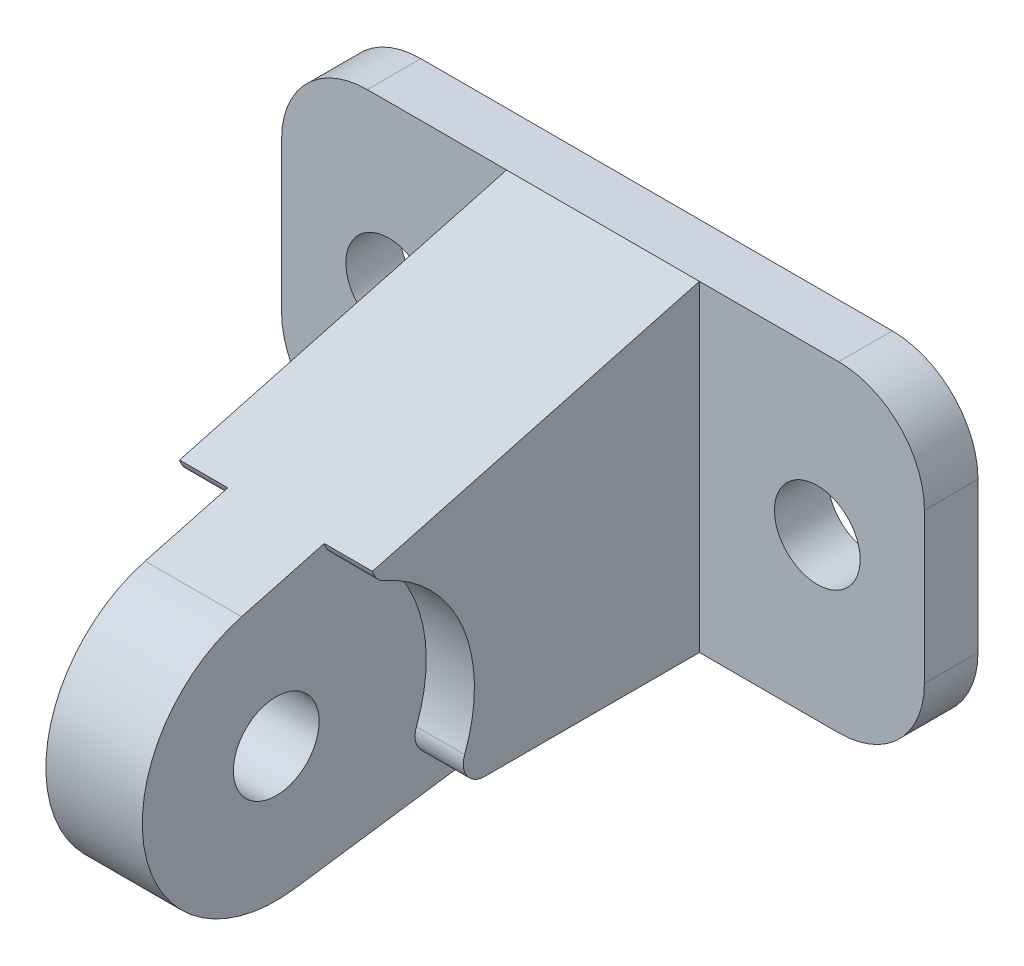
SolidWorks part; units mm, degrees
ref_plane "Płaszczyzna przednia" through (0, 0, 0) normal (0, 0, 1) x (1, 0, 0)
ref_plane "Płaszczyzna górna" through (0, 0, 0) normal (0, 1, 0) x (1, 0, 0)
ref_plane "Płaszczyzna prawa" through (0, 0, 0) normal (1, 0, 0) x (0, 0, -1)
sketch "Szkic1" plane through (0, 0, 0) normal (0, 0, 1) x (1, 0, 0)
  line L1 (-22, 15) -> (22, 15)
  line L2 (-30, 7) -> (-30, -7)
  line L3 (-22, -15) -> (22, -15)
  line L4 (30, 7) -> (30, -7)
  line L5 (-30, 15) -> (30, -15) construction
  line L6 (-30, -15) -> (30, 15) construction
  arc A0 (22, -15) -> (30, -7) centre (22, -7) ccw
  arc A1 (30, 7) -> (22, 15) centre (22, 7) ccw
  arc A2 (-22, -15) -> (-30, -7) centre (-22, -7) cw
  arc A3 (-22, 15) -> (-30, 7) centre (-22, 7) ccw
  circle A4 centre (-20, 0) radius 4
  circle A5 centre (20, 0) radius 4
  point P0 (0, 0)
  point P22 (0, 0)
  point P23 (0, 0)
  dimension "D3" = 8
  dimension "D4" = 8
  dimension "D5" = 8
  dimension "D1" = 30
  dimension "D2" = 60
  dimension "D6" = 40
  dimension "20" = 20
extrude "Dodanie-wyciągnięcie1" add sketch "Szkic1" along normal blind 5
sketch "Szkic7" plane through (0, 0, 0) normal (1, 0, 0) x (0, 0, -1)
  line L0 (-5, 15) -> (-43.2352, 4.7549)
  line L1 (-38.2519, -19.6963) -> (-5, -15)
  line L2 (-5, -15) -> (-5, 15)
  arc A0 (-43.2352, 4.7549) -> (-38.2519, -19.6963) centre (-40, -7.3192) ccw
  circle A1 centre (-40, -7.3192) radius 4
  point P9 (0, 0)
  dimension "D2" = 8
  dimension "12,5" = 12.5
  dimension "D1" = 75
  dimension "D3" = 35
extrude "Dodanie-wyciągnięcie3" add sketch "Szkic7" along normal mid plane 9
sketch "Szkic8" plane through (4.5, 0, 0) normal (1, 0, 0) x (0, 0, -1)
  line L0 (-5, 15) -> (-35.5199, 6.8222)
  line L1 (-5, 15) -> (-43.2352, 4.7549) construction
  line L2 (-25.0425, -15) -> (-5, -15)
  line L3 (-5, -15) -> (-5, 15) construction
  arc A0 (-35.5199, 6.8222) -> (-34.3896, 5.5075) centre (-33.5881, 7.3399) ccw
  arc A1 (-34.3896, 5.5075) -> (-26.9121, -12.2899) centre (-40, -7.3192) cw
  arc A2 (-25.0425, -15) -> (-26.9121, -12.2899) centre (-25.0425, -13) cw
  circle A4 centre (-40, -7.3192) radius 4 construction
  circle A5 centre (-40, -7.3192) radius 4
  line M3 (-5, -15) -> (-5, 15)
  line M4 (-5, 15) -> (-43.2352, 4.7549)
  dimension "D1" = 14
  dimension "D2" = 2
  dimension "D3" = 2
extrude "Dodanie-wyciągnięcie5" add sketch "Szkic8" along normal blind 4.5 and the other way blind 13.5 contours A2 L2 A0 A1 M3 M4
